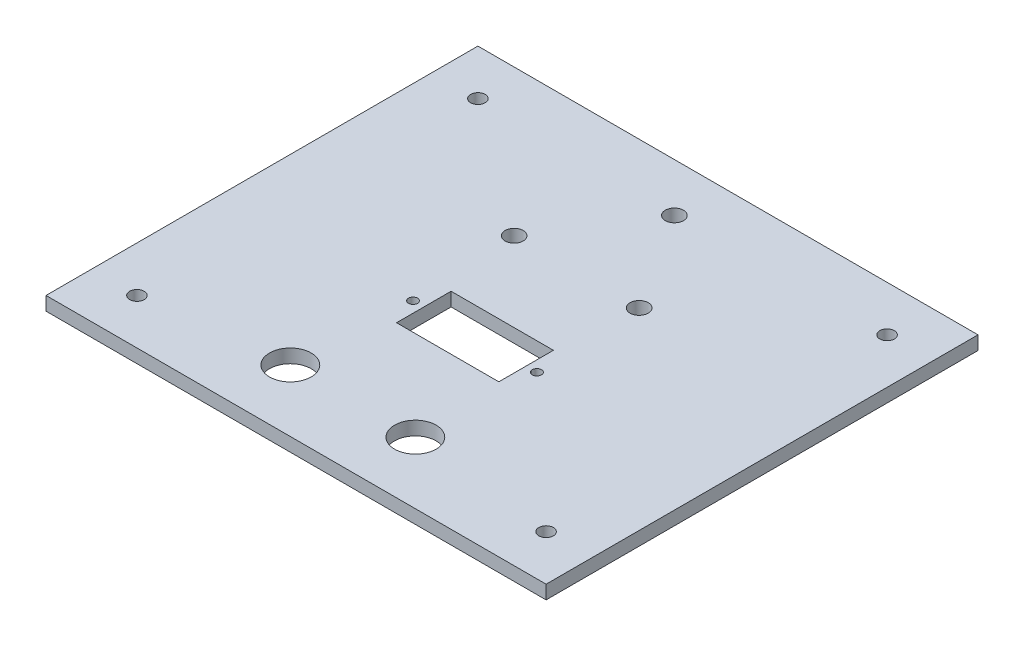
SolidWorks part; units mm, degrees
ref_plane "Front Plane" through (0, 0, 0) normal (0, 0, 1) x (1, 0, 0)
ref_plane "Top Plane" through (0, 0, 0) normal (0, 1, 0) x (1, 0, 0)
ref_plane "Right Plane" through (0, 0, 0) normal (1, 0, 0) x (0, 0, -1)
sketch "Sketch1" plane through (0, 0, 0) normal (0, 1, 0) x (1, 0, 0)
  line L0 (-55, 47.5) -> (55, -47.5)
  line L1 (-55, 47.5) -> (55, 47.5)
  line L2 (-55, 47.5) -> (-55, -47.5)
  line L3 (-55, -47.5) -> (55, -47.5)
  line L4 (55, 47.5) -> (55, -47.5)
  line L5 (55, 47.5) -> (-55, -47.5)
  line L6 (-1.135, 26.0556) -> (-1.135, 7.9735) construction
  circle A0 centre (-1.135, 36.8556) radius 2
  circle A1 centre (-14.885, 15.3556) radius 2
  circle A2 centre (12.615, 15.3556) radius 2
  point P4 (0, 0)
  dimension "D1" = 110
  dimension "D2" = 95
extrude "Boss-Extrude1" add sketch "Sketch1" along normal blind 3 contours L5 L1 L0 | L5 L0 L2 | L0 L5 L3 | L4 L5 L0
sketch "Sketch2" plane through (0, 3, 0) normal (0, 1, 0) x (1, 0, 0)
  line L0 (-55, 47.5) -> (-55, -47.5) construction
  line L1 (-55, 47.5) -> (55, 47.5) construction
  line L2 (55, 47.5) -> (55, -47.5) construction
  line L3 (-55, -47.5) -> (55, -47.5) construction
  circle A0 centre (-45, 37.5) radius 1.6
  circle A1 centre (45, 37.5) radius 1.6
  circle A2 centre (-45, -37.5) radius 1.6
  circle A3 centre (45, -37.5) radius 1.6
  dimension "D1" = 3.2
  dimension "D2" = 10
  dimension "D3" = 10
  dimension "D4" = 10
  dimension "D5" = 10
  dimension "D6" = 10
  dimension "D7" = 10
  dimension "D8" = 10
  dimension "D9" = 10
extrude "Cut-Extrude1" cut sketch "Sketch2" against normal blind 3
sketch "Sketch4" plane through (0, 3, 0) normal (0, 1, 0) x (1, 0, 0)
  line L0 (-14.885, 15.3556) -> (-14.885, -33.8697) construction
  line L1 (12.615, -33.8697) -> (12.615, 15.3556) construction
  line L2 (-14.885, -33.8697) -> (12.615, -33.8697) construction
  circle A0 centre (-14.885, -33.8697) radius 4.575
  circle A1 centre (12.615, -33.8697) radius 4.575
  dimension "D1" = 9.15
extrude "Cut-Extrude3" cut sketch "Sketch4" against normal blind 3 contours A0 | A1
sketch "Sketch5" plane through (0, 3, 0) normal (0, 1, 0) x (1, 0, 0)
  line L0 (-11.25, -2.1471) -> (11.25, -14.1471)
  line L1 (-11.25, -2.1471) -> (11.25, -2.1471)
  line L2 (-11.25, -2.1471) -> (-11.25, -14.1471)
  line L3 (-11.25, -14.1471) -> (11.25, -14.1471)
  line L4 (11.25, -2.1471) -> (11.25, -14.1471)
  line L5 (11.25, -2.1471) -> (-11.25, -14.1471)
  line L6 (-13.625, -8.1471) -> (13.625, -8.1471) construction
  circle A0 centre (-13.625, -8.1471) radius 1
  circle A1 centre (13.625, -8.1471) radius 1
  point P4 (0, -8.1471)
  dimension "D3" = 2
  dimension "D1" = 22.5
  dimension "D2" = 12
  dimension "D4" = 27.25
extrude "Cut-Extrude4" cut sketch "Sketch5" against normal blind 10
